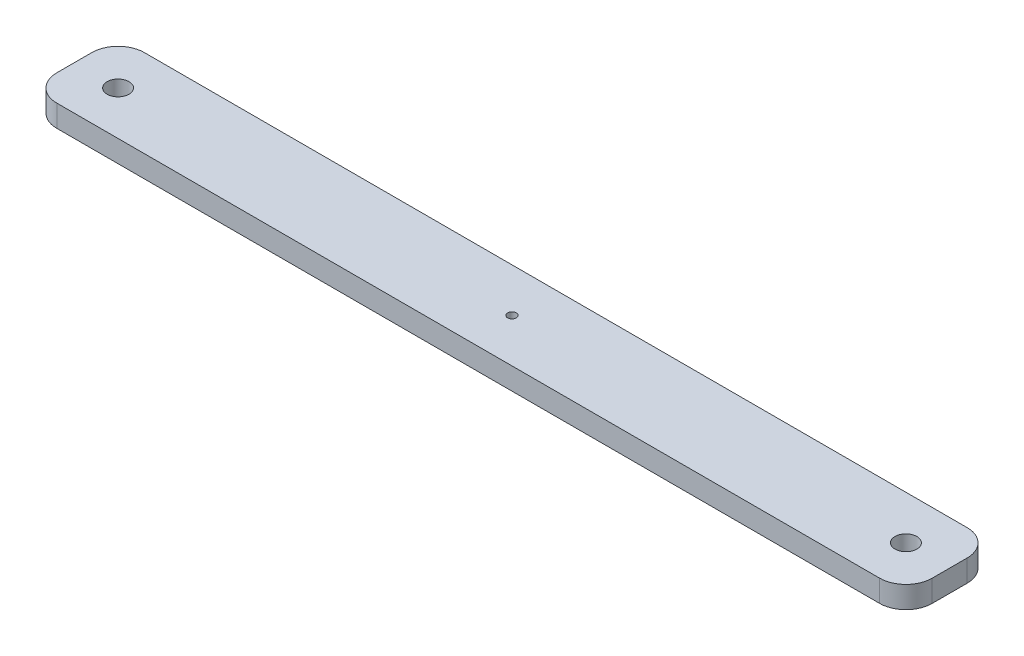
SolidWorks part; units mm, degrees
ref_plane "Front Plane" through (0, 0, 0) normal (0, 0, 1) x (1, 0, 0)
ref_plane "Top Plane" through (0, 0, 0) normal (0, 1, 0) x (1, 0, 0)
ref_plane "Right Plane" through (0, 0, 0) normal (1, 0, 0) x (0, 0, -1)
sketch "Sketch1" plane through (0, 0, 0) normal (0, 1, 0) x (1, 0, 0)
  line L1 (7.62, 0) -> (246.38, 0)
  line L2 (0, -7.62) -> (0, -17.78)
  line L3 (7.62, -25.4) -> (246.38, -25.4)
  line L4 (254, -7.62) -> (254, -17.78)
  circle A0 centre (12.7, -12.7) radius 3.175
  circle A1 centre (241.3, -12.7) radius 3.175
  circle A2 centre (127, -12.7) radius 1.27
  arc A3 (254, -7.62) -> (246.38, 0) centre (246.38, -7.62) ccw
  arc A4 (254, -17.78) -> (246.38, -25.4) centre (246.38, -17.78) cw
  arc A5 (7.62, 0) -> (0, -7.62) centre (7.62, -7.62) ccw
  arc A6 (0, -17.78) -> (7.62, -25.4) centre (7.62, -17.78) ccw
  point P17 (0, 0)
  dimension "D1" = 7.62
extrude "Boss-Extrude1" add sketch "Sketch1" along normal blind 6.35
